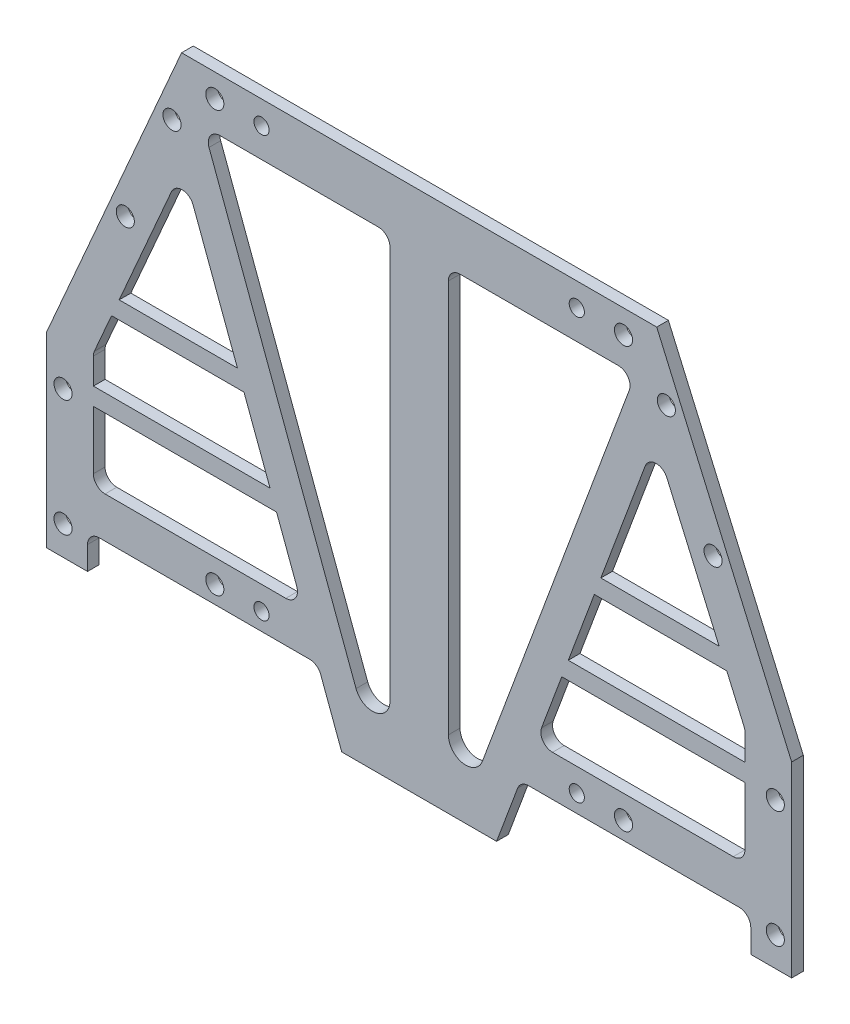
SolidWorks part; units mm, degrees
ref_plane "前视基准面" through (0, 0, 0) normal (0, 0, 1) x (1, 0, 0)
ref_plane "上视基准面" through (0, 0, 0) normal (0, 1, 0) x (1, 0, 0)
ref_plane "右视基准面" through (0, 0, 0) normal (1, 0, 0) x (0, 0, -1)
sketch "草图1" plane through (0, 0, 0) normal (0, 0, 1) x (1, 0, 0)
  line L0 (0, 0) -> (12.8351, 41.9818) construction
  line L1 (-48, 0) -> (48, 0) construction
  line L2 (-48, 0) -> (-48, 105.1) construction
  line L3 (-48, 105.1) -> (48, 105.1)
  line L4 (48, 0) -> (48, 105.1) construction
  line L5 (0, 0) -> (-17.1531, 40.4102) construction
  line L6 (0, 0) -> (0, 40.9) construction
  line L7 (-9.5, 52.6) -> (9.5, 52.6) construction
  line L8 (-45.9553, -13.8603) -> (-66, 52.6)
  line L9 (-14, 101.6) -> (14, 101.6) construction
  line L10 (-66, 52.6) -> (-66, 105.1)
  line L11 (0, 0) -> (0, 52.6) construction
  line L12 (0, 52.6) -> (0, 101.6) construction
  line L13 (-66, 105.1) -> (-48, 105.1)
  line L14 (48, 105.1) -> (66, 105.1)
  line L15 (66, 105.1) -> (66, 52.6)
  line L16 (66, 52.6) -> (45.9553, -13.8603)
  arc A0 (-45.9553, -13.8603) -> (45.9553, -13.8603) centre (0, 0) ccw
  circle A1 centre (0, 0) radius 40.9
  circle A2 centre (12.8351, 41.9818) radius 1.525
  circle A3 centre (-17.1531, 40.4102) radius 1.525
  circle A4 centre (0, 0) radius 44.9 construction
  circle A5 centre (-31.7491, 31.7491) radius 1.525
  circle A6 centre (31.7491, 31.7491) radius 1.525
  circle A7 centre (31.7491, -31.7491) radius 1.525
  circle A8 centre (-31.7491, -31.7491) radius 1.525
  circle A9 centre (-14, 101.6) radius 2.1 construction
  circle A10 centre (14, 101.6) radius 2.1 construction
  circle A11 centre (-9.5, 52.6) radius 1.525
  circle A12 centre (9.5, 52.6) radius 1.525
  point P24 (0, 0)
  dimension "D2" = 96
  dimension "D3" = 81.8
  dimension "D8" = 89.8
  dimension "D9" = 3.05
  dimension "D14" = 4.2
  dimension "D1" = 105.1
  dimension "D4" = 43.9
  dimension "D5" = 17
  dimension "D6" = 40
  dimension "D10" = 52.6
  dimension "D11" = 19
  dimension "D12" = 28
  dimension "D13" = 49
  dimension "D15" = 132
  dimension "D7" = 4
extrude "凸台-拉伸1" add sketch "草图1" along normal blind 2
sketch "草图3" plane through (0, 0, 2) normal (0, 0, 1) x (1, 0, 0)
  line L0 (-66, 105.1) -> (-42, 160.1)
  line L1 (-42, 160.1) -> (-22, 160.1)
  line L2 (-22, 160.1) -> (-22, 105.1) construction
  line L3 (66, 105.1) -> (-66, 105.1) construction
  line L4 (-22, 105.1) -> (-66, 105.1)
  line L5 (0, 105.1) -> (0, 160.1) construction
  line L6 (22, 160.1) -> (22, 105.1) construction
  line L7 (42, 160.1) -> (22, 160.1)
  line L8 (66, 105.1) -> (42, 160.1)
  line L9 (22, 105.1) -> (66, 105.1)
  line L10 (-22, 160.1) -> (22, 160.1)
  line L11 (22, 105.1) -> (-22, 105.1)
  dimension "D1" = 22
  dimension "D2" = 55
  dimension "D3" = 20
extrude "凸台-拉伸2" add sketch "草图3" against normal up to surface (2 mm away) up to face at (0, 42.2566, 0)
sketch "草图4" plane through (0, 0, 2) normal (0, 0, 1) x (1, 0, 0)
  line L0 (-66, 105.1) -> (-61, 105.1) construction
  line L1 (-61, 105.1) -> (-61, 100.1) construction
  line L2 (-61, 100.1) -> (-61, 80.1) construction
  line L3 (-42, 160.1) -> (-38.3338, 158.5002) construction
  line L4 (-38.3338, 158.5002) -> (-42.3333, 149.3348) construction
  line L5 (-42.3333, 149.3348) -> (-50.3322, 131.004) construction
  line L6 (42, 160.1) -> (-42, 160.1) construction
  line L7 (-42, 160.1) -> (-66, 105.1) construction
  line L8 (0, 0) -> (0, 160.1) construction
  circle A0 centre (-61, 100.1) radius 1.55
  circle A1 centre (-61, 80.1) radius 1.55
  circle A2 centre (-42.3333, 149.3348) radius 1.55
  circle A3 centre (-50.3322, 131.004) radius 1.55
  circle A4 centre (61, 80.1) radius 1.55
  circle A5 centre (61, 100.1) radius 1.55
  circle A6 centre (50.3322, 131.004) radius 1.55
  circle A7 centre (42.3333, 149.3348) radius 1.55
  dimension "D5" = 3.1
  dimension "D1" = 5
  dimension "D2" = 5
  dimension "D3" = 20
  dimension "D4" = 10
  dimension "D6" = 4
extrude "切除-拉伸2" cut sketch "草图4" against normal blind 10
sketch "草图5" plane through (0, 0, 2) normal (0, 0, 1) x (1, 0, 0)
  line L0 (-40.6907, 160.1) -> (-63.8, 107.1413)
  line L1 (-63.8, 107.1413) -> (-63.8, 70.1)
  line L2 (-63.8, 70.1) -> (63.8, 70.1)
  line L3 (63.8, 70.1) -> (63.8, 107.1413)
  line L4 (63.8, 107.1413) -> (40.6907, 160.1)
  line L5 (40.6907, 160.1) -> (-40.6907, 160.1)
  line L6 (42, 160.1) -> (-42, 160.1) construction
  line L8 (66, 52.6) -> (66, 105.1) construction
  line L10 (-66, 105.1) -> (-66, 52.6) construction
  line L11 (-42, 160.1) -> (-66, 105.1) construction
  line L12 (66, 105.1) -> (42, 160.1) construction
  dimension "D1" = 2.2
  dimension "D2" = 2.2
  dimension "D3" = 1.2
  dimension "D4" = 1.2
  dimension "D5" = 90
extrude "切除-拉伸3" cut sketch "草图5" against normal blind 10 flip side to cut
sketch "草图7" plane through (0, 0, 0) normal (0, 0, -1) x (-1, 0, 0)
  line L0 (0, 160.1) -> (0, 156.1) construction
  line L1 (-27, 156.1) -> (27, 156.1) construction
  line L2 (-27, 156.1) -> (-27, 84.1) construction
  line L3 (-27, 84.1) -> (27, 84.1) construction
  line L4 (27, 156.1) -> (27, 84.1) construction
  line L5 (40.6907, 160.1) -> (-40.6907, 160.1) construction
  line L6 (-27, 156.1) -> (-35, 156.1) construction
  line L7 (27, 156.1) -> (35, 156.1) construction
  line L8 (-27, 84.1) -> (-35, 84.1) construction
  line L9 (27, 84.1) -> (35, 84.1) construction
  circle A0 centre (-27, 156.1) radius 1.3
  circle A1 centre (27, 156.1) radius 1.3
  circle A2 centre (-27, 84.1) radius 1.3
  circle A3 centre (27, 84.1) radius 1.3
  circle A4 centre (-35, 156.1) radius 1.55
  circle A5 centre (35, 156.1) radius 1.55
  circle A6 centre (-35, 84.1) radius 1.55
  circle A7 centre (35, 84.1) radius 1.55
  dimension "D4" = 2.6
  dimension "D6" = 3.1
  dimension "D1" = 54
  dimension "D2" = 72
  dimension "D3" = 4
  dimension "D5" = 8
extrude "切除-拉伸4" cut sketch "草图7" against normal blind 10
sketch "草图8" plane through (0, 0, 0) normal (0, 0, -1) x (-1, 0, 0)
  line L0 (-34.1218, 151.1) -> (-7, 151.1)
  line L1 (-5, 149.1) -> (-5, 81.7651)
  line L2 (-10.8117, 80.7189) -> (-35.9963, 148.4025)
  line L3 (-38.7195, 138.5161) -> (-20.9637, 90.7975)
  line L4 (-22.8382, 88.1) -> (-53.8, 88.1)
  line L5 (-55.8, 90.1) -> (-55.8, 107.5548)
  line L6 (-55.6331, 108.3547) -> (-42.427, 138.6185)
  line L7 (-56.8, 79.1) -> (-56.8, 67.1)
  line L8 (-54.8, 65.1) -> (-14.2801, 65.1)
  line L9 (-12.4056, 67.7975) -> (-16.8707, 79.7975)
  line L10 (-18.7452, 81.1) -> (-54.8, 81.1)
  line L11 (-63.8, 70.1) -> (-63.8, 107.1413) construction
  line L12 (-40.6907, 160.1) -> (40.6907, 160.1) construction
  line L13 (-63.8, 107.1413) -> (-40.6907, 160.1) construction
  line L14 (0, 160.1) -> (0, 70.1) construction
  line L15 (40.6907, 160.1) -> (-40.6907, 160.1) construction
  line L16 (63.8, 107.1413) -> (63.8, 70.1) construction
  line L17 (18.7452, 81.1) -> (54.8, 81.1)
  line L18 (12.4056, 67.7975) -> (16.8707, 79.7975)
  line L19 (54.8, 65.1) -> (14.2801, 65.1)
  line L20 (56.8, 79.1) -> (56.8, 67.1)
  line L21 (55.6331, 108.3547) -> (42.427, 138.6185)
  line L22 (55.8, 90.1) -> (55.8, 107.5548)
  line L23 (22.8382, 88.1) -> (53.8, 88.1)
  line L24 (38.7195, 138.5161) -> (20.9637, 90.7975)
  line L25 (10.8117, 80.7189) -> (35.9963, 148.4025)
  line L26 (5, 149.1) -> (5, 81.7651)
  line L27 (34.1218, 151.1) -> (7, 151.1)
  line L28 (63.8, 70.1) -> (-63.8, 70.1) construction
  circle A0 centre (-35, 84.1) radius 1.55 construction
  arc A1 (-5, 81.7651) -> (-10.8117, 80.7189) centre (-8, 81.7651) cw
  arc A2 (-16.8707, 79.7975) -> (-18.7452, 81.1) centre (-18.7452, 79.1) ccw
  arc A3 (-14.2801, 65.1) -> (-12.4056, 67.7975) centre (-14.2801, 67.1) ccw
  arc A4 (-56.8, 67.1) -> (-54.8, 65.1) centre (-54.8, 67.1) ccw
  arc A5 (-55.8, 107.5548) -> (-55.6331, 108.3547) centre (-53.8, 107.5548) cw
  arc A6 (-53.8, 88.1) -> (-55.8, 90.1) centre (-53.8, 90.1) cw
  arc A7 (-56.8, 79.1) -> (-54.8, 81.1) centre (-54.8, 79.1) cw
  arc A8 (-20.9637, 90.7975) -> (-22.8382, 88.1) centre (-22.8382, 90.1) cw
  arc A9 (-38.7195, 138.5161) -> (-42.427, 138.6185) centre (-40.594, 137.8186) ccw
  arc A10 (-7, 151.1) -> (-5, 149.1) centre (-7, 149.1) cw
  arc A11 (-34.1218, 151.1) -> (-35.9963, 148.4025) centre (-34.1218, 149.1) ccw
  arc A12 (34.1218, 151.1) -> (35.9963, 148.4025) centre (34.1218, 149.1) cw
  arc A13 (7, 151.1) -> (5, 149.1) centre (7, 149.1) ccw
  arc A14 (38.7195, 138.5161) -> (42.427, 138.6185) centre (40.594, 137.8186) cw
  arc A15 (20.9637, 90.7975) -> (22.8382, 88.1) centre (22.8382, 90.1) ccw
  arc A16 (56.8, 79.1) -> (54.8, 81.1) centre (54.8, 79.1) ccw
  arc A17 (53.8, 88.1) -> (55.8, 90.1) centre (53.8, 90.1) ccw
  arc A18 (55.8, 107.5548) -> (55.6331, 108.3547) centre (53.8, 107.5548) ccw
  arc A19 (56.8, 67.1) -> (54.8, 65.1) centre (54.8, 67.1) cw
  arc A20 (14.2801, 65.1) -> (12.4056, 67.7975) centre (14.2801, 67.1) cw
  arc A21 (16.8707, 79.7975) -> (18.7452, 81.1) centre (18.7452, 79.1) cw
  arc A22 (5, 81.7651) -> (10.8117, 80.7189) centre (8, 81.7651) ccw
  point P25 (-5, 65.1)
  point P44 (-5, 151.1)
  point P47 (-37, 151.1)
  dimension "D1" = 3
  dimension "D11" = 3
  dimension "D12" = 2
  dimension "D2" = 4
  dimension "D3" = 8
  dimension "D4" = 7
  dimension "D5" = 6
  dimension "D6" = 10
  dimension "D7" = 9
  dimension "D8" = 32
  dimension "D9" = 95
  dimension "D10" = 7
extrude "切除-拉伸5" cut sketch "草图8" against normal blind 10
sketch "草图9" plane through (0, 0, 0) normal (0, 0, -1) x (-1, 0, 0)
  line L6 (-55.8, 107.5548) -> (-55.8, 90.1) construction
  line L7 (-55.8, 115.1) -> (-30.0066, 115.1)
  line L8 (-55.8, 115.1) -> (-55.8, 118.1)
  line L9 (-55.8, 118.1) -> (-30.0066, 118.1)
  line L10 (-30.0066, 115.1) -> (-30.0066, 118.1)
  line L11 (-20.9637, 90.7975) -> (-38.7195, 138.5161) construction
  line L12 (-53.8, 88.1) -> (-22.8382, 88.1) construction
  line L13 (-55.8, 100.1) -> (-24.4252, 100.1)
  line L14 (-55.8, 100.1) -> (-55.8, 103.1)
  line L15 (-55.8, 103.1) -> (-24.4252, 103.1)
  line L16 (-24.4252, 100.1) -> (-24.4252, 103.1)
  line L17 (0, 160.1) -> (0, 168.323) construction
  line L18 (40.6907, 160.1) -> (-40.6907, 160.1) construction
  line L19 (24.4252, 100.1) -> (24.4252, 103.1)
  line L20 (55.8, 103.1) -> (24.4252, 103.1)
  line L21 (55.8, 100.1) -> (55.8, 103.1)
  line L22 (55.8, 100.1) -> (24.4252, 100.1)
  line L23 (30.0066, 115.1) -> (30.0066, 118.1)
  line L24 (55.8, 118.1) -> (30.0066, 118.1)
  line L25 (55.8, 115.1) -> (55.8, 118.1)
  line L26 (55.8, 115.1) -> (30.0066, 115.1)
  dimension "D1" = 12
  dimension "D2" = 3
  dimension "D3" = 3
  dimension "D4" = 12
extrude "凸台-拉伸4" add sketch "草图9" against normal up to surface (2 mm away) up to face at (0, 88.8163, 2)
sketch "草图12" plane through (0, 0, 0) normal (0, 0, -1) x (-1, 0, 0)
  line L1 (-63.8, 70.1) -> (-43.8, 70.1)
  line L2 (-63.8, 70.1) -> (-63.8, 75.1)
  line L3 (-63.8, 75.1) -> (-43.8, 75.1)
  line L4 (-43.8, 70.1) -> (-43.8, 75.1)
  line L5 (63.8, 70.1) -> (43.8, 70.1)
  line L6 (63.8, 70.1) -> (63.8, 75.1)
  line L7 (63.8, 75.1) -> (43.8, 75.1)
  line L8 (43.8, 70.1) -> (43.8, 75.1)
  dimension "D1" = 20
  dimension "D2" = 5
extrude "切除-拉伸7" cut sketch "草图12" against normal blind 10
